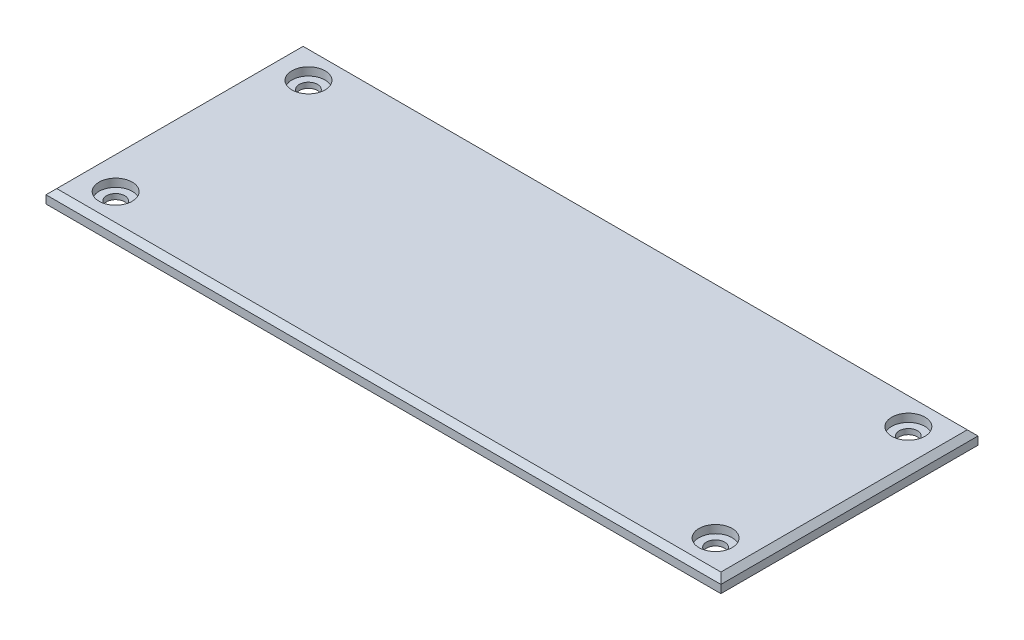
SolidWorks part; units mm, degrees
ref_plane "Front Plane" through (0, 0, 0) normal (0, 0, 1) x (1, 0, 0)
ref_plane "Top Plane" through (0, 0, 0) normal (0, 1, 0) x (1, 0, 0)
ref_plane "Right Plane" through (0, 0, 0) normal (1, 0, 0) x (0, 0, -1)
ref_plane "Plane1" through (0, 25.5, 0) normal (0, 1, 0) x (1, 0, 0)
sketch "Sketch1" plane through (0, 25.5, 0) normal (0, 1, 0) x (1, 0, 0)
  line L0 (-63, 24) -> (63, 24)
  line L1 (63, 24) -> (63, -24)
  line L2 (63, -24) -> (-63, -24)
  line L3 (-63, -24) -> (-63, 24)
extrude "Boss-Extrude1" add sketch "Sketch1" along normal blind 2.5
chamfer "Chamfer1" distance 1 angle 45 4 edges at (0, 28, 24) (63, 28, 0) (0, 28, -24) (-63, 28, 0)
sketch "Sketch2" plane through (0, 25.5, 0) normal (0, 1, 0) x (1, 0, 0)
  line L0 (-59.7, 20.7) -> (59.7, 20.7)
  line L1 (59.7, 20.7) -> (59.7, -20.7)
  line L2 (59.7, -20.7) -> (-59.7, -20.7)
  line L3 (-59.7, -20.7) -> (-59.7, 20.7)
  line L4 (-58.1, 19.1) -> (58.1, 19.1)
  line L5 (58.1, 19.1) -> (58.1, -19.1)
  line L6 (58.1, -19.1) -> (-58.1, -19.1)
  line L7 (-58.1, -19.1) -> (-58.1, 19.1)
extrude "Boss-Extrude2" add sketch "Sketch2" against normal blind 1.2
sketch "Sketch3" plane through (0, 25.5, 0) normal (0, 1, 0) x (1, 0, 0)
  circle A0 centre (-56, 18) radius 4.5
  circle A1 centre (-56, -18) radius 4.5
  circle A2 centre (56, 18) radius 4.5
  circle A3 centre (56, -18) radius 4.5
extrude "Cut-Extrude1" cut sketch "Sketch3" against normal blind 1.5
ref_plane "Plane2" through (0, 28, 0) normal (0, 1, 0) x (1, 0, 0)
sketch "Sketch4" plane through (0, 28, 0) normal (0, 1, 0) x (1, 0, 0)
  circle A0 centre (-56, 18) radius 1.7
  circle A1 centre (-56, -18) radius 1.7
  circle A2 centre (56, 18) radius 1.7
  circle A3 centre (56, -18) radius 1.7
extrude "Cut-Extrude2" cut sketch "Sketch4" against normal through all
sketch "Sketch5" plane through (0, 28, 0) normal (0, 1, 0) x (1, 0, 0)
  circle A0 centre (-56, 18) radius 3.1
  circle A1 centre (-56, -18) radius 3.1
  circle A2 centre (56, 18) radius 3.1
  circle A3 centre (56, -18) radius 3.1
extrude "Cut-Extrude3" cut sketch "Sketch5" against normal blind 1.5
